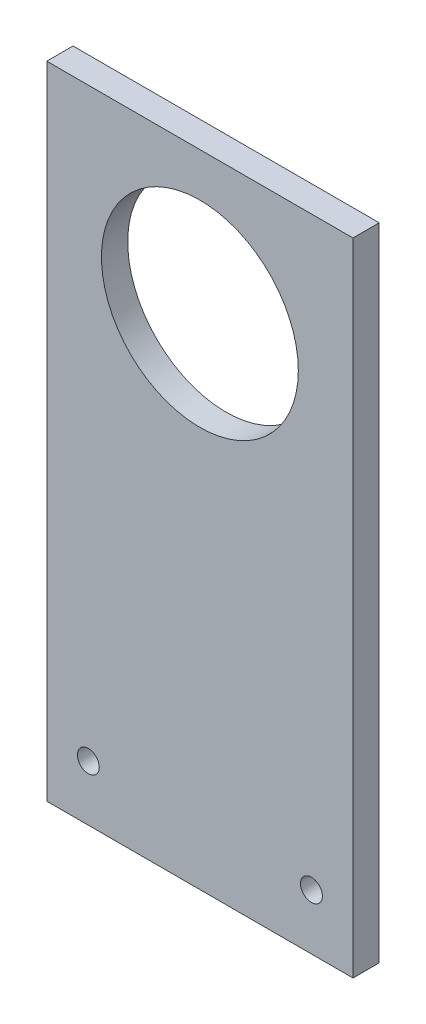
SolidWorks part; units mm, degrees
ref_plane "Front Plane" through (0, 0, 0) normal (0, 0, 1) x (1, 0, 0)
ref_plane "Top Plane" through (0, 0, 0) normal (0, 1, 0) x (1, 0, 0)
ref_plane "Right Plane" through (0, 0, 0) normal (1, 0, 0) x (0, 0, -1)
sketch "Sketch2" plane through (0, 0, 0) normal (0, 0, 1) x (1, 0, 0)
  line L0 (-55, 104.5) -> (55, 104.5) construction
  line L1 (-35, 0) -> (35, 0)
  line L2 (-35, 0) -> (-35, 114)
  line L3 (-35, 114) -> (35, 114) construction
  line L4 (35, 0) -> (35, 114)
  line L5 (0, 104.5) -> (0, 0) construction
  line L6 (0, 104.5) -> (0, 114) construction
  line L11 (35, 114) -> (35, 146.5)
  line L12 (35, 146.5) -> (-35, 146.5)
  line L13 (-35, 146.5) -> (-35, 114)
  circle A0 centre (-55, 104.5) radius 3 construction
  circle A1 centre (55, 104.5) radius 3 construction
  circle A2 centre (-55, 104.5) radius 16 construction
  circle A3 centre (55, 104.5) radius 16 construction
  circle A6 centre (0, 114) radius 22.5
  point P6 (0, 0)
  dimension "D1" = 6
  dimension "D2" = 32
  dimension "D5" = 45
  dimension "D3" = 110
  dimension "D4" = 9.5
  dimension "D6" = 70
  dimension "D7" = 104.5
  dimension "D8" = 32.5
extrude "Boss-Extrude1" add sketch "Sketch2" along normal mid plane 6
sketch "Sketch3" plane through (0, 0, 3) normal (0, 0, 1) x (1, 0, 0)
  line L1 (-35, 0) -> (-25.5, 0) construction
  line L2 (-35, 0) -> (-35, 12.7) construction
  line L3 (-35, 12.7) -> (-25.5, 12.7) construction
  line L4 (-25.5, 0) -> (-25.5, 12.7) construction
  line L5 (35, 0) -> (25.5, 0) construction
  line L6 (35, 0) -> (35, 12.7) construction
  line L7 (35, 12.7) -> (25.5, 12.7) construction
  line L8 (25.5, 0) -> (25.5, 12.7) construction
  circle A0 centre (-25.5, 12.7) radius 2.5
  circle A1 centre (25.5, 12.7) radius 2.5
  dimension "D1" = 12.7
  dimension "D2" = 5
  dimension "D3" = 9.5
extrude "Cut-Extrude1" cut sketch "Sketch3" against normal blind 6
